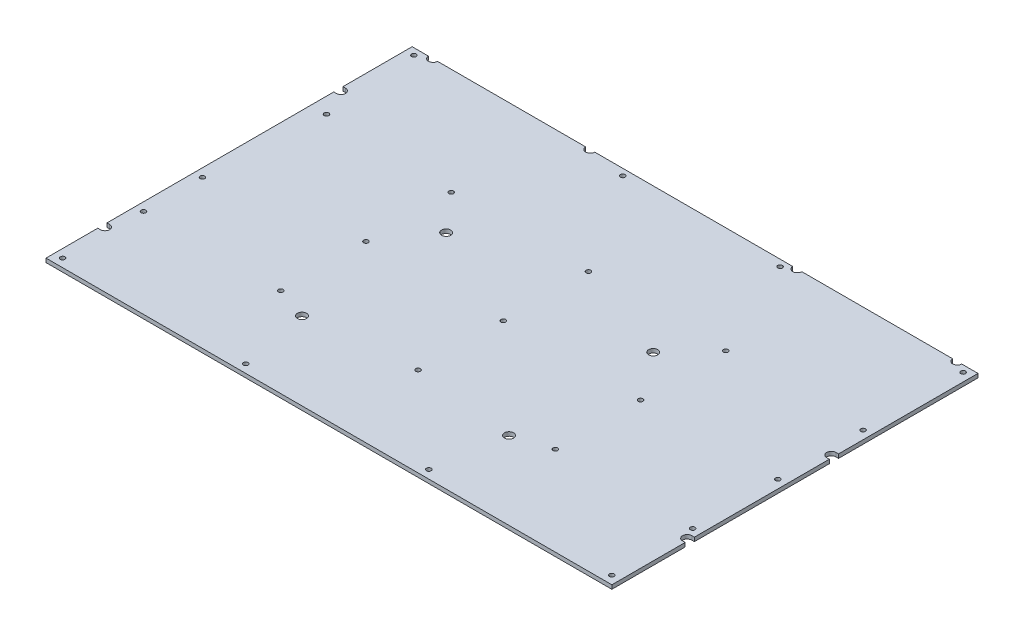
SolidWorks part; units mm, degrees
ref_plane "Front Plane" through (0, 0, 0) normal (0, 0, 1) x (1, 0, 0)
ref_plane "Top Plane" through (0, 0, 0) normal (0, 1, 0) x (1, 0, 0)
ref_plane "Right Plane" through (0, 0, 0) normal (1, 0, 0) x (0, 0, -1)
sketch "Sketch1" plane through (0, 0, 0) normal (0, 1, 0) x (1, 0, 0)
  line L1 (-215.9, -147.35) -> (215.9, -147.35)
  line L2 (-215.9, -147.35) -> (-215.9, 147.35)
  line L3 (-215.9, 147.35) -> (215.9, 147.35)
  line L4 (215.9, -147.35) -> (215.9, 147.35)
  line L5 (-215.9, -147.35) -> (215.9, 147.35) construction
  line L6 (-215.9, 147.35) -> (215.9, -147.35) construction
  point P0 (0, 0)
  dimension "D1" = 294.7
  dimension "D2" = 431.8
extrude "Boss-Extrude1" add sketch "Sketch1" along normal blind 3
sketch "Sketch2" plane through (0, 3, 0) normal (0, 1, 0) x (1, 0, 0)
  line L0 (-215.9, 147.35) -> (-215.9, -147.35) construction
  line L1 (-215.9, -147.35) -> (215.9, -147.35) construction
  line L2 (215.9, 147.35) -> (-215.9, 147.35) construction
  circle A0 centre (-209.55, -125.7) radius 1.775
  circle A1 centre (-209.55, 142.35) radius 1.775
  dimension "D3" = 3.55
  dimension "D5" = 6.35
  dimension "D6" = 3.55
  dimension "D1" = 6.35
  dimension "D2" = 21.65
  dimension "D4" = 5
extrude "Cut-Extrude1" cut sketch "Sketch2" against normal through all
pattern_linear "LPattern1" count 4 spacing 139.7 along (1, 0, 0) of "Cut-Extrude1"
sketch "Sketch3" plane through (0, 3, 0) normal (0, 1, 0) x (1, 0, 0)
  line L0 (-209.55, -64) -> (-209.55, -125.7) construction
  line L1 (215.9, 147.35) -> (-215.9, 147.35) construction
  circle A0 centre (-209.55, -64) radius 1.775
  dimension "D2" = 3.55
  dimension "D1" = 211.35
extrude "Cut-Extrude2" cut sketch "Sketch3" against normal through all
pattern_linear "LPattern2" count 5 spacing 104.77 along (1, 0, 0) count 3 spacing 65 along (0, 0, -1) skipping (0, 1), (0, 2) of "Cut-Extrude2"
sketch "Sketch4" plane through (0, 3, 0) normal (0, 1, 0) x (1, 0, 0)
  line L0 (-209.55, -19) -> (-209.55, -64) construction
  line L1 (-215.9, 147.35) -> (-215.9, -147.35) construction
  circle A0 centre (-203.9, 70) radius 1.775
  circle A2 centre (-104.78, 66) radius 1.775 construction
  circle A3 centre (-209.55, -64) radius 1.775 construction
  circle A4 centre (-209.55, -19) radius 1.775
  dimension "D1" = 4
  dimension "D2" = 45
  dimension "D3" = 12
extrude "Cut-Extrude3" cut sketch "Sketch4" against normal blind 10
sketch "Sketch7" plane through (0, 0, 0) normal (0, -1, 0) x (1, 0, 0)
  line L0 (215.9, -147.35) -> (-215.9, -147.35) construction
  circle A0 centre (-213.9, -91.0361) radius 3.5
  circle A1 centre (-213.9, 89.0115) radius 3.5
  circle A2 centre (-200, 140.04) radius 3.5 construction
  circle A3 centre (-80, 140.04) radius 3.5 construction
  circle A4 centre (78, 140.04) radius 3.5 construction
  circle A5 centre (200, 140.04) radius 3.5 construction
  circle A6 centre (213.9, 72.58) radius 3.5
  circle A7 centre (213.9, -37.42) radius 3.5
  circle A8 centre (200, -147.42) radius 3.5
  circle A9 centre (78, -147.42) radius 3.5
  circle A10 centre (-80, -147.42) radius 3.5
  circle A11 centre (-80, -37.42) radius 3.5
  circle A12 centre (78, -37.42) radius 3.5
  circle A13 centre (78, 72.58) radius 3.5
  circle A14 centre (-80, 72.58) radius 3.5
  circle A15 centre (-200, -147.42) radius 3.5
  dimension "D1" = 7
  dimension "D2" = 56.3139
extrude "Cut-Extrude5" cut sketch "Sketch7" against normal through all
sketch "Sketch8" plane through (0, 3, 0) normal (0, 1, 0) x (1, 0, 0)
  line L0 (215.9, 40.2923) -> (215.9, 147.35) construction
  line L1 (213.9, 33.92) -> (215.9, 33.92)
  line L2 (213.9, 33.92) -> (213.9, 40.92)
  line L3 (213.9, 40.92) -> (215.9, 40.92)
  line L4 (215.9, 33.92) -> (215.9, 40.92)
  line L5 (215.9, -69.7077) -> (215.9, 34.5477) construction
  line L6 (213.9, -69.08) -> (215.9, -69.08)
  line L7 (213.9, -69.08) -> (213.9, -76.08)
  line L8 (213.9, -76.08) -> (215.9, -76.08)
  line L9 (215.9, -69.08) -> (215.9, -76.08)
  line L10 (-215.9, 88.1638) -> (-215.9, -86.1392) construction
  line L11 (-213.9, 94.5361) -> (-215.9, 94.5361)
  line L12 (-213.9, 94.5361) -> (-213.9, 87.5361)
  line L13 (-213.9, 87.5361) -> (-215.9, 87.5361)
  line L14 (-215.9, 94.5361) -> (-215.9, 87.5361)
  line L15 (-215.9, -91.8837) -> (-215.9, -147.35) construction
  line L16 (-213.9, -85.5115) -> (-215.9, -85.5115)
  line L17 (-213.9, -85.5115) -> (-213.9, -92.5115)
  line L18 (-213.9, -92.5115) -> (-215.9, -92.5115)
  line L19 (-215.9, -85.5115) -> (-215.9, -92.5115)
  arc A0 (215.9, 40.2923) -> (215.9, 34.5477) centre (213.9, 37.42) ccw construction
  arc A1 (215.9, -69.7077) -> (215.9, -75.4523) centre (213.9, -72.58) ccw construction
  arc A2 (-215.9, 88.1638) -> (-215.9, 93.9083) centre (-213.9, 91.0361) ccw construction
  arc A3 (-215.9, -91.8837) -> (-215.9, -86.1392) centre (-213.9, -89.0115) ccw construction
extrude "Cut-Extrude6" cut sketch "Sketch8" against normal through all
sketch "Sketch9" plane through (0, 0, 0) normal (0, -1, 0) x (1, 0, 0)
  line L0 (-215.9, 92.5115) -> (-215.9, 147.35) construction
  line L1 (215.9, 147.35) -> (-215.9, 147.35)
  line L2 (215.9, 147.35) -> (215.9, 132.05)
  line L3 (215.9, 132.05) -> (-215.9, 132.05)
  line L4 (-215.9, 147.35) -> (-215.9, 132.05)
  dimension "D1" = 15.3
extrude "Cut-Extrude7" cut sketch "Sketch9" against normal through all
sketch "Sketch11" plane through (0, 3, 0) normal (0, 1, 0) x (1, 0, 0)
  circle A0 centre (-69.85, 142.35) radius 1.775 construction
  circle A1 centre (-69.85, 142.35) radius 1.775
extrude "Boss-Extrude3" add sketch "Sketch11" against normal up to surface (3 mm away) up to face at (-0.1429, 0, -37.9692)
sketch "Sketch12" plane through (0, 3, 0) normal (0, 1, 0) x (1, 0, 0)
  line L0 (-50.15, 142.35) -> (69.85, 142.35) construction
  circle A0 centre (-50.15, 142.35) radius 1.775
  circle A1 centre (69.85, 142.35) radius 1.775 construction
  dimension "D1" = 120
extrude "Cut-Extrude8" cut sketch "Sketch12" against normal through all
